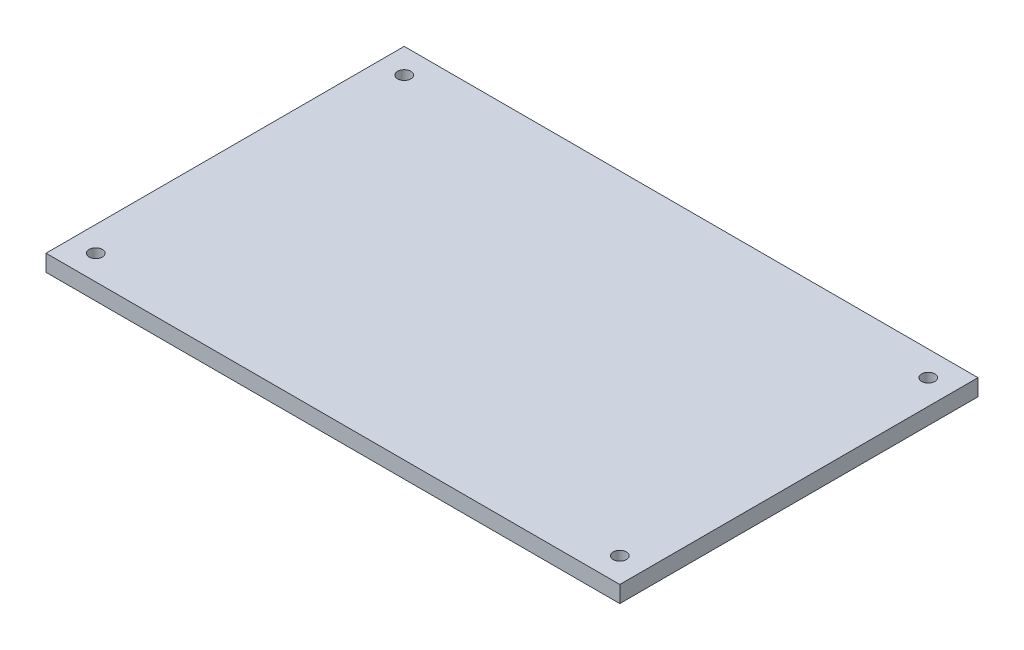
SolidWorks part; units mm, degrees
ref_plane "前视基准面" through (0, 0, 0) normal (0, 0, 1) x (1, 0, 0)
ref_plane "上视基准面" through (0, 0, 0) normal (0, 1, 0) x (1, 0, 0)
ref_plane "右视基准面" through (0, 0, 0) normal (1, 0, 0) x (0, 0, -1)
other "Configuration Table"
sketch "草图1" plane through (0, 0, 0) normal (0, 1, 0) x (1, 0, 0)
  line L0 (0, 54) -> (0, 0) construction
  line L1 (-86.5, -54) -> (86.5, -54)
  line L2 (-86.5, -54) -> (-86.5, 54)
  line L3 (-86.5, 54) -> (86.5, 54)
  line L4 (86.5, -54) -> (86.5, 54)
  line L5 (-86.5, -54) -> (86.5, 54) construction
  line L6 (-86.5, 54) -> (86.5, -54) construction
  line L7 (0, 0) -> (86.5, 0) construction
  circle A0 centre (-79, 46.5) radius 2
  circle A1 centre (79, 46.5) radius 2
  circle A2 centre (79, -46.5) radius 2
  circle A3 centre (-79, -46.5) radius 2
  point P0 (0, 0)
  dimension "D1" = 7.5
  dimension "D3" = 4
  dimension "D6" = 158
  dimension "D2" = 7.5
  dimension "D4" = 79
  dimension "D5" = 46.5
extrude "凸台-拉伸1" add sketch "草图1" along normal blind 5
sketch "草图2" plane through (0, 0, -54) normal (0, 0, -1) x (-1, 0, 0)
  line L0 (-86.5, 0) -> (86.5, 0) construction
  line L1 (-42.5, 0) -> (-22.5, 0)
  line L2 (-42.5, 0) -> (-42.5, -10.2)
  line L3 (-42.5, -10.2) -> (-22.5, -10.2)
  line L4 (-22.5, 0) -> (-22.5, -10.2)
  line L5 (22.5, 0) -> (42.5, 0)
  line L6 (22.5, 0) -> (22.5, -10.2)
  line L7 (22.5, -10.2) -> (42.5, -10.2)
  line L8 (42.5, 0) -> (42.5, -10.2)
  circle A0 centre (-32.5, -5.2) radius 1.75
  circle A1 centre (32.5, -5.2) radius 1.75
  dimension "D3" = 5.2
  dimension "D4" = 3.5
  dimension "D1" = 20
  dimension "D2" = 10.2
  dimension "D5" = 10
  dimension "D6" = 22.5
  dimension "D7" = 2
extrude "凸台-拉伸2" add sketch "草图2" against normal blind 30
fillet "圆角1" radius 1 8 edges at (42.5, -10.2, -39) (22.5, -10.2, -39) (-22.5, -10.2, -39) (-42.5, -10.2, -39) (-42.5, 0, -39) (-22.5, 0, -39) (42.5, 0, -39) (22.5, 0, -39)
sketch "草图3" plane through (0, 0, -24) normal (0, 0, 1) x (1, 0, 0)
  line L0 (23.5, -10.2) -> (41.5, -10.2) construction
  line L1 (42.5, -9.2) -> (42.5, -1) construction
  line L2 (43.5, 0) -> (21.5, 0) construction
  line L3 (22.5, -1) -> (22.5, -9.2) construction
  line L4 (-41.5, -10.2) -> (-23.5, -10.2) construction
  line L5 (-22.5, -9.2) -> (-22.5, -1) construction
  line L6 (-21.5, 0) -> (-43.5, 0) construction
  line L7 (-42.5, -1) -> (-42.5, -9.2) construction
  line L8 (23.5, -10.2) -> (41.5, -10.2)
  line L9 (42.5, -9.2) -> (42.5, -1)
  line L10 (43.5, 0) -> (21.5, 0)
  line L11 (22.5, -1) -> (22.5, -9.2)
  line L12 (-41.5, -10.2) -> (-23.5, -10.2)
  line L13 (-22.5, -9.2) -> (-22.5, -1)
  line L14 (-21.5, 0) -> (-43.5, 0)
  line L15 (-42.5, -1) -> (-42.5, -9.2)
  arc A0 (41.5, -10.2) -> (42.5, -9.2) centre (41.5, -9.2) ccw construction
  arc A1 (43.5, 0) -> (42.5, -1) centre (43.5, -1) ccw construction
  arc A2 (22.5, -1) -> (21.5, 0) centre (21.5, -1) ccw construction
  arc A3 (22.5, -9.2) -> (23.5, -10.2) centre (23.5, -9.2) ccw construction
  arc A4 (-23.5, -10.2) -> (-22.5, -9.2) centre (-23.5, -9.2) ccw construction
  arc A5 (-21.5, 0) -> (-22.5, -1) centre (-21.5, -1) ccw construction
  arc A6 (-42.5, -1) -> (-43.5, 0) centre (-43.5, -1) ccw construction
  arc A7 (-42.5, -9.2) -> (-41.5, -10.2) centre (-41.5, -9.2) ccw construction
  arc A8 (41.5, -10.2) -> (42.5, -9.2) centre (41.5, -9.2) ccw
  arc A9 (43.5, 0) -> (42.5, -1) centre (43.5, -1) ccw
  arc A10 (22.5, -1) -> (21.5, 0) centre (21.5, -1) ccw
  arc A11 (22.5, -9.2) -> (23.5, -10.2) centre (23.5, -9.2) ccw
  arc A12 (-23.5, -10.2) -> (-22.5, -9.2) centre (-23.5, -9.2) ccw
  arc A13 (-21.5, 0) -> (-22.5, -1) centre (-21.5, -1) ccw
  arc A14 (-42.5, -1) -> (-43.5, 0) centre (-43.5, -1) ccw
  arc A15 (-42.5, -9.2) -> (-41.5, -10.2) centre (-41.5, -9.2) ccw
  circle A16 centre (32.5, -5.2) radius 1.75 construction
  circle A17 centre (-32.5, -5.2) radius 1.75 construction
  circle A18 centre (32.5, -5.2) radius 1.75
  circle A19 centre (-32.5, -5.2) radius 1.75
extrude "凸台-拉伸3" add sketch "草图3" along normal blind 6.5
